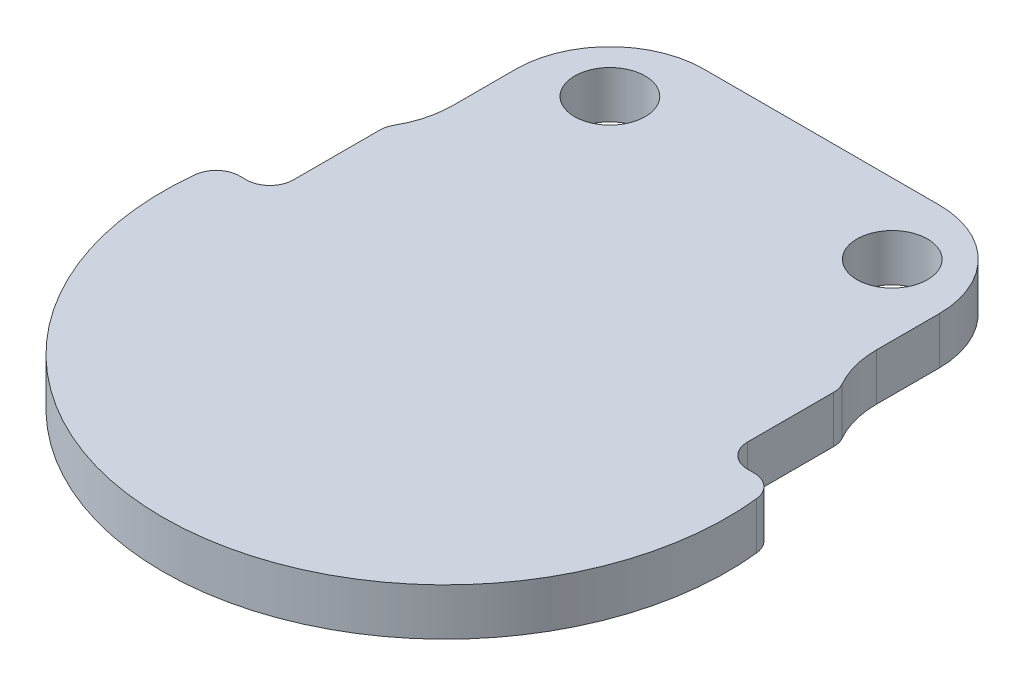
SolidWorks part; units mm, degrees
ref_plane "Спереди" through (0, 0, 0) normal (0, 0, 1) x (1, 0, 0)
ref_plane "Сверху" through (0, 0, 0) normal (0, 1, 0) x (1, 0, 0)
ref_plane "Справа" through (0, 0, 0) normal (1, 0, 0) x (0, 0, -1)
sketch "Sketch1" plane through (0, 0, 0) normal (0, 1, 0) x (1, 0, 0)
  line L0 (0, 0) -> (0, 13) construction
  line L1 (0, 13) -> (6, 13) construction
  line L2 (0, 13) -> (-6, 13) construction
  line L3 (-9, 10) -> (-9, 7.9373)
  line L4 (-9, 16) -> (9, 16)
  line L5 (-9, 16) -> (-9, 10)
  line L6 (-9, 10) -> (9, 10) construction
  line L7 (9, 16) -> (9, 10)
  line L8 (-9, 16) -> (9, 10) construction
  line L9 (-9, 10) -> (9, 16) construction
  line L10 (9, 10) -> (9, 7.9373)
  circle A0 centre (0, 0) radius 10 construction
  arc A1 (-9, 7.9373) -> (9, 7.9373) centre (0, 0) ccw
  circle A2 centre (-6, 13) radius 1.5
  circle A3 centre (6, 13) radius 1.5
  dimension "D1" = 20
  dimension "D2" = 2
  dimension "D3" = 3
  dimension "D5" = 3
  dimension "D6" = 12
  dimension "D7" = 3
extrude "Boss-Extrude1" add sketch "Sketch1" along normal blind 2
fillet "Fillet2" radius 4 4 edges at (-9, 1, -7.9373) (-9, 1, -16) (9, 1, -16) (9, 1, -7.9373)
sketch "Sketch2" plane through (0, 2, 0) normal (0, 1, 0) x (1, 0, 0)
  line L0 (-10.15, 2.7) -> (-10.15, 6.4014) construction
  line L1 (-10.15, 2.7) -> (-10.15, 19.2) construction
  line L2 (-10.15, 2.7) -> (-11.6923, 2.7) construction
  line L3 (-10.15, 2.7) -> (-22.85, 2.7) construction
  line L4 (0, 0) -> (0, 16) construction
  line L5 (5, 16) -> (-5, 16) construction
  line L6 (-11.7966, 2.2) -> (-9.65, 2.2)
  line L7 (-9.65, 2.2) -> (-9.65, 7.2557)
  line L8 (9.65, 2.2) -> (9.65, 7.2557)
  line L9 (11.7966, 2.2) -> (9.65, 2.2)
  arc A0 (-9.75, 6.9955) -> (9.75, 6.9955) centre (0, 0) ccw construction
  arc A2 (9.65, 7.2557) -> (11.7966, 2.2) centre (3.4809, 1.6528) cw
  arc A9 (-9.65, 7.2557) -> (-11.7966, 2.2) centre (-3.4809, 1.6528) ccw
  dimension "D1" = 0.5
  dimension "D2" = 0.5
extrude "Cut-Extrude1" cut sketch "Sketch2" against normal through all
fillet "Fillet3" radius 1 6 edges at (-9.65, 1, -2.2) (9.65, 1, -2.2) (11.7966, 1, -2.2) (9.65, 1, -7.1416) (-9.65, 1, -7.1416) (-11.7966, 1, -2.2)
